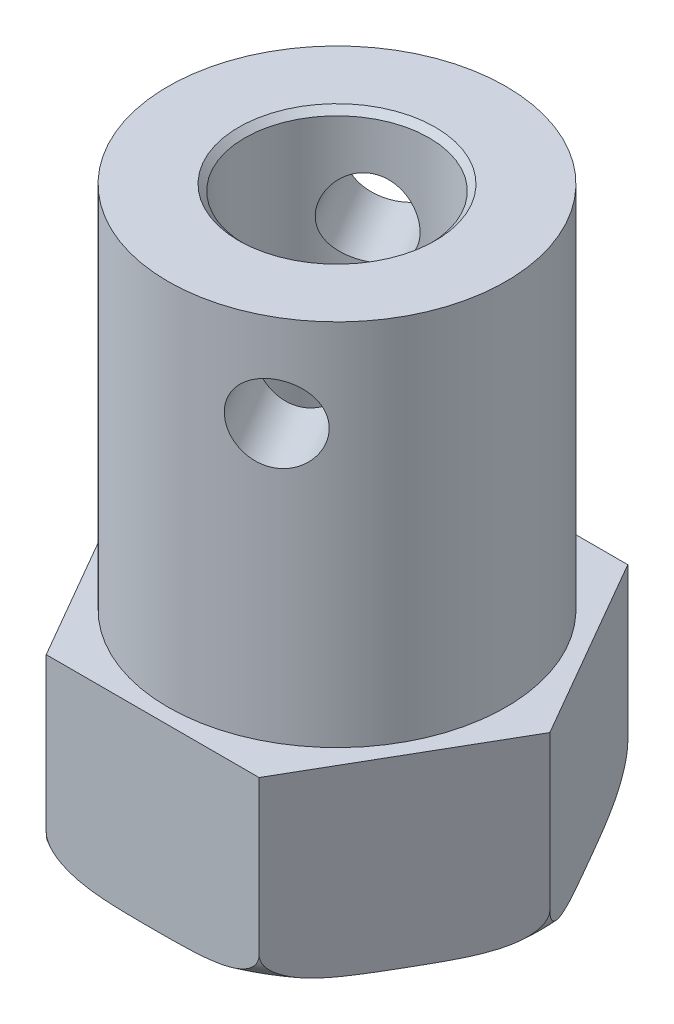
SolidWorks part; units mm, degrees
material "Chrome Stainless Steel"
ref_plane "Front Plane" through (0, 0, 0) normal (0, 0, 1) x (1, 0, 0)
ref_plane "Top Plane" through (0, 0, 0) normal (0, 1, 0) x (1, 0, 0)
ref_plane "Right Plane" through (0, 0, 0) normal (1, 0, 0) x (0, 0, -1)
sketch "Sketch1" plane through (0, 0, 0) normal (0, 1, 0) x (1, 0, 0)
  line L1 (3.4641, -6) -> (6.9282, 0)
  line L2 (6.9282, 0) -> (3.4641, 6)
  line L3 (3.4641, 6) -> (-3.4641, 6)
  line L4 (-3.4641, 6) -> (-6.9282, 0)
  line L5 (-6.9282, 0) -> (-3.4641, -6)
  line L6 (-3.4641, -6) -> (3.4641, -6)
  circle A0 centre (0, 0) radius 6 construction
  dimension "D1" = 12
extrude "BASE" add sketch "Sketch1" along normal blind 6
sketch "Sketch2" plane through (0, 6, 0) normal (0, 1, 0) x (1, 0, 0)
  line L1 (0, 5.5) -> (0, 6) construction
  line L2 (3.4641, 6) -> (-3.4641, 6) construction
  circle A0 centre (0, 0) radius 5.5
  dimension "D1" = 0.5
  dimension "D2" = 11
extrude "SHAFT HOLDING BODY" add sketch "Sketch2" along normal blind 12
hole_wizard "M4x0.7 Tapped Hole1" positions "Sketch3" profile "Sketch4" tap size "M4x0.7" standard "ANSI Metric" end condition through all
sketch "Sketch3" plane through (0, 0, 0) normal (0, -1, 0) x (-1, 0, 0)
  point P0 (0, 0)
sketch "Sketch4" plane through (0, 0, 0) normal (1, 0, 0) x (0, 0, -1)
  line L0 (0, 0) -> (0, 18)
  line L1 (0, 18) -> (1.65, 18)
  line L2 (1.65, 18) -> (1.65, 0.35)
  line L3 (1.65, 0.35) -> (2, 0)
  line L5 (2, 0) -> (0, 0)
  line L6 (-1.65, 0.35) -> (-2, 0) construction
  line L11 (0, -6.35) -> (0, 107.95) construction
  dimension "Thru Tap Drill Dia." = 3.3
  dimension "Thru Tap Drill Depth" = 18
  dimension "Near C'Sink Dia." = 4
  dimension "Near C'Sink Angle" = 90
cosmetic thread "Hole Thread3" parameters "D2"=4
ref_plane "SET SCREW REFERENCE PLANE" through (2.75, 6, 4.7631) normal (0.5, 0, 0.866) x (0.866, 0, -0.5)
hole_wizard "M3x0.5 Tapped Hole1" positions "Sketch7" profile "Sketch8" tap size "M3x0.5" standard "ANSI Metric" end condition through all
sketch "Sketch7" plane through (2.75, 6, 4.7631) normal (0.5, 0, 0.866) x (0.866, 0, -0.5)
  line L0 (5.5, 12) -> (-5.5, 12) construction
  line L1 (0, 12) -> (0, 0) construction
  line L2 (0, 12) -> (0, 9) construction
  point P0 (0, 9)
  dimension "D1" = 3
sketch "Sketch8" plane through (2.75, 15, 4.7631) normal (0, 1, 0) x (0.866, 0, -0.5)
  line L0 (0, 0) -> (0, 14.1603)
  line L1 (0, 14.1603) -> (1.25, 14.1603)
  line L2 (1.25, 14.1603) -> (1.25, 0)
  line L5 (1.25, 0) -> (0, 0)
  line L11 (0, -6.35) -> (0, 107.95) construction
  dimension "Thru Tap Drill Dia." = 2.5
  dimension "Thru Tap Drill Depth" = 14.1603
cosmetic thread "Hole Thread2" parameters "D2"=3
sketch "Sketch9" plane through (0, 0, 0) normal (0, 0, 1) x (1, 0, 0)
  line L0 (-6.9282, 1) -> (-6.9282, 0)
  line L1 (-6.9282, 0) -> (-5.9282, 0)
  line L2 (6, 0) -> (-6, 0) construction
  line L4 (-6.9282, 6) -> (-6.9282, 0) construction
  arc A0 (-6.9282, 1) -> (-5.9282, 0) centre (-5.9282, 1) ccw
  dimension "D1" = 1
revolve "BASE CHAMFER RELIEF" cut sketch "Sketch9" angle 360 about axis through (0, 0, 0) along (0, -1, 0)
sketch "Sketch13" plane through (0, 18, 0) normal (0, 1, 0) x (1, 0, 0)
  circle A0 centre (0, 0) radius 3
  dimension "D1" = 6
extrude "SHAFT HOLE" cut sketch "Sketch13" against normal offset from surface (13.5 mm away) 4.5 up to face at (0, 0, -2)
chamfer "SH C" distance 0.2 angle 45 1 edges at (0, 18, 3)
